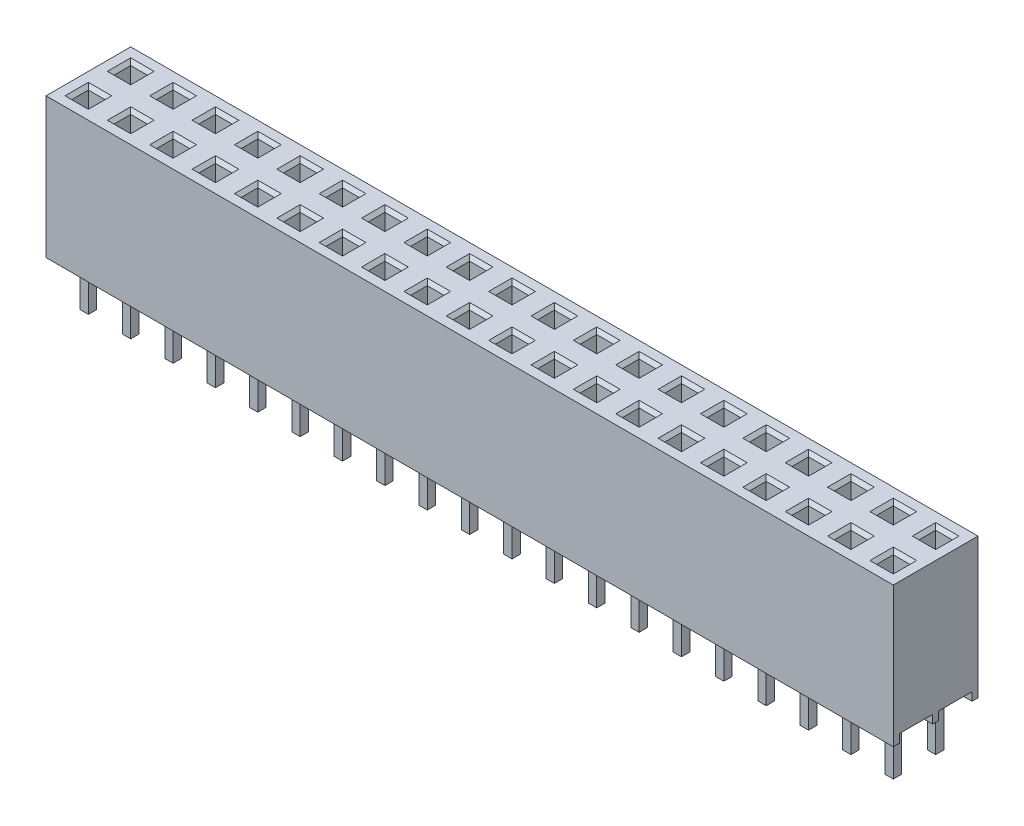
SolidWorks part; units mm, degrees
ref_plane "Спереди" through (0, 0, 0) normal (0, 0, 1) x (1, 0, 0)
ref_plane "Сверху" through (0, 0, 0) normal (0, 1, 0) x (1, 0, 0)
ref_plane "Справа" through (0, 0, 0) normal (1, 0, 0) x (0, 0, -1)
sketch "Эскиз1" plane through (0, 0, 0) normal (0, 1, 0) x (1, 0, 0)
  line L0 (0, 2.54) -> (0, -2.54) construction
  line L1 (-6.35, 2.54) -> (6.35, 2.54)
  line L2 (-6.35, 2.54) -> (-6.35, -2.54)
  line L3 (-6.35, -2.54) -> (6.35, -2.54)
  line L4 (6.35, 2.54) -> (6.35, -2.54)
  line L6 (6.35, 0) -> (-6.35, 0) construction
  dimension "D1" = 12.7
  dimension "D2" = 5.08
extrude "Бобышка-Вытянуть1" add sketch "Эскиз1" along normal blind 8.4
sketch "Эскиз2" plane through (6.35, 0, 0) normal (1, 0, 0) x (0, 0, -1)
  line L0 (-2.54, 0) -> (2.54, 0) construction
  line L1 (-2.18, 0) -> (-0.18, 0)
  line L2 (-2.18, 0) -> (-2.18, 0.5)
  line L3 (-2.18, 0.5) -> (-0.18, 0.5)
  line L4 (-0.18, 0) -> (-0.18, 0.5)
  line L5 (0, 0) -> (0, 8.4) construction
  line L6 (-2.54, 8.4) -> (-2.54, 0) construction
  line L10 (0.18, 0) -> (2.18, 0)
  line L11 (0.18, 0) -> (0.18, 0.5)
  line L12 (0.18, 0.5) -> (2.18, 0.5)
  line L13 (2.18, 0) -> (2.18, 0.5)
  line L14 (-2.54, 8.4) -> (2.54, 8.4) construction
  dimension "D1" = 0.5
  dimension "D2" = 0.36
  dimension "D3" = 0.36
extrude "Вырез-Вытянуть1" cut sketch "Эскиз2" against normal up to next
sketch "Эскиз3" plane through (0, 0.5, 0) normal (0, -1, 0) x (1, 0, 0)
  line L0 (-6.35, 0) -> (6.35, 0) construction
  line L1 (-6.35, 2.18) -> (-6.35, 0.18) construction
  line L3 (-5.08, 1.77) -> (-5.08, 0.77) construction
  line L4 (-5.58, 1.77) -> (-4.58, 1.77)
  line L5 (-5.58, 1.77) -> (-5.58, 0.77)
  line L6 (-5.58, 0.77) -> (-4.58, 0.77)
  line L7 (-4.58, 1.77) -> (-4.58, 0.77)
  line L8 (-5.58, 1.27) -> (-4.58, 1.27) construction
  line L9 (-6.35, -0.18) -> (-6.35, 0.18) construction
  line L10 (6.35, 0.18) -> (6.35, -0.18) construction
  line L11 (-5.58, -1.27) -> (-4.58, -1.27) construction
  line L12 (-5.08, -1.77) -> (-5.08, -0.77) construction
  line L13 (-4.58, -1.77) -> (-4.58, -0.77)
  line L14 (-5.58, -0.77) -> (-4.58, -0.77)
  line L15 (-5.58, -1.77) -> (-5.58, -0.77)
  line L16 (-5.58, -1.77) -> (-4.58, -1.77)
  line L17 (-3.04, 1.77) -> (-3.04, 0.77)
  line L18 (-3.04, 1.77) -> (-2.04, 1.77)
  line L19 (-2.04, 1.77) -> (-2.04, 0.77)
  line L20 (-3.04, 0.77) -> (-2.04, 0.77)
  line L21 (-3.04, -0.77) -> (-2.04, -0.77)
  line L22 (-3.04, -1.77) -> (-3.04, -0.77)
  line L23 (-3.04, -1.77) -> (-2.04, -1.77)
  line L24 (-2.04, -1.77) -> (-2.04, -0.77)
  line L25 (-0.5, 1.77) -> (-0.5, 0.77)
  line L26 (-0.5, 1.77) -> (0.5, 1.77)
  line L27 (0.5, 1.77) -> (0.5, 0.77)
  line L28 (-0.5, 0.77) -> (0.5, 0.77)
  line L29 (-0.5, -0.77) -> (0.5, -0.77)
  line L30 (-0.5, -1.77) -> (-0.5, -0.77)
  line L31 (-0.5, -1.77) -> (0.5, -1.77)
  line L32 (0.5, -1.77) -> (0.5, -0.77)
  line L33 (2.04, 1.77) -> (2.04, 0.77)
  line L34 (2.04, 1.77) -> (3.04, 1.77)
  line L35 (3.04, 1.77) -> (3.04, 0.77)
  line L36 (2.04, 0.77) -> (3.04, 0.77)
  line L37 (2.04, -0.77) -> (3.04, -0.77)
  line L38 (2.04, -1.77) -> (2.04, -0.77)
  line L39 (2.04, -1.77) -> (3.04, -1.77)
  line L40 (3.04, -1.77) -> (3.04, -0.77)
  line L41 (4.58, 1.77) -> (4.58, 0.77)
  line L42 (4.58, 1.77) -> (5.58, 1.77)
  line L43 (5.58, 1.77) -> (5.58, 0.77)
  line L44 (4.58, 0.77) -> (5.58, 0.77)
  line L45 (4.58, -0.77) -> (5.58, -0.77)
  line L46 (4.58, -1.77) -> (4.58, -0.77)
  line L47 (4.58, -1.77) -> (5.58, -1.77)
  line L48 (5.58, -1.77) -> (5.58, -0.77)
  line L49 (-5.58, 1.77) -> (-3.04, 1.77) construction
  dimension "D1" = 1
  dimension "D2" = 1
  dimension "D3" = 1.27
  dimension "D4" = 2.54
  dimension "D6" = 2.54
  dimension "D5" = 5
extrude "Вырез-Вытянуть2" cut sketch "Эскиз3" against normal up to next
chamfer "Фаска1" distance 0.2 angle 45 40 edges at (-5.08, 8.4, 1.77) (-4.58, 8.4, 1.27) (-5.08, 8.4, 0.77) (-5.58, 8.4, 1.27) (-2.04, 8.4, 1.27) (-2.54, 8.4, 0.77) (-3.04, 8.4, 1.27) (-2.54, 8.4, 1.77) (0.5, 8.4, 1.27) (0, 8.4, 0.77) (-0.5, 8.4, 1.27) (0, 8.4, 1.77) (3.04, 8.4, 1.27) (2.54, 8.4, 0.77) (2.04, 8.4, 1.27) (2.54, 8.4, 1.77) (5.58, 8.4, 1.27) (5.08, 8.4, 0.77) (4.58, 8.4, 1.27) (5.08, 8.4, 1.77) (5.08, 8.4, -1.77) (4.58, 8.4, -1.27) (5.08, 8.4, -0.77) (5.58, 8.4, -1.27) (2.54, 8.4, -1.77) (2.04, 8.4, -1.27) (2.54, 8.4, -0.77) (3.04, 8.4, -1.27) (0, 8.4, -1.77) (-0.5, 8.4, -1.27) (0, 8.4, -0.77) (0.5, 8.4, -1.27) (-2.54, 8.4, -1.77) (-3.04, 8.4, -1.27) (-2.54, 8.4, -0.77) (-2.04, 8.4, -1.27) (-5.58, 8.4, -1.27) (-5.08, 8.4, -0.77) (-4.58, 8.4, -1.27) (-5.08, 8.4, -1.77)
pattern_linear "Линейный массив3" count 4 spacing 12.7 along (1, 0, 0) of "Бобышка-Вытянуть1", "Вырез-Вытянуть1", "Фаска1", "Вырез-Вытянуть2"
sketch "Эскиз4" plane through (0, 0.5, 0) normal (0, -1, 0) x (1, 0, 0)
  line L0 (-5.08, 1.52) -> (-5.08, 1.02) construction
  line L1 (-5.33, 1.52) -> (-4.83, 1.52)
  line L2 (-5.33, 1.52) -> (-5.33, 1.02)
  line L3 (-5.33, 1.02) -> (-4.83, 1.02)
  line L4 (-4.83, 1.52) -> (-4.83, 1.02)
  line L5 (-5.33, -1.27) -> (-4.83, -1.27) construction
  line L6 (-5.33, 1.27) -> (-4.83, 1.27) construction
  line L7 (-5.08, -1.52) -> (-5.08, -1.02) construction
  line L8 (-6.35, -0.18) -> (-6.35, 0.18) construction
  line L9 (-6.35, 0) -> (44.45, 0) construction
  line L11 (-4.83, -1.52) -> (-4.83, -1.02)
  line L12 (-5.33, -1.02) -> (-4.83, -1.02)
  line L13 (-5.33, -1.52) -> (-5.33, -1.02)
  line L14 (-5.33, -1.52) -> (-4.83, -1.52)
  line L15 (-6.35, 2.18) -> (-6.35, 0.18) construction
  line L16 (-2.79, 1.52) -> (-2.79, 1.02)
  line L17 (-2.79, 1.52) -> (-2.29, 1.52)
  line L18 (-2.79, 1.02) -> (-2.29, 1.02)
  line L19 (-2.29, 1.52) -> (-2.29, 1.02)
  line L20 (-2.79, -1.52) -> (-2.29, -1.52)
  line L21 (-2.79, -1.52) -> (-2.79, -1.02)
  line L22 (-2.79, -1.02) -> (-2.29, -1.02)
  line L23 (-2.29, -1.52) -> (-2.29, -1.02)
  line L24 (-0.25, 1.52) -> (-0.25, 1.02)
  line L25 (-0.25, 1.52) -> (0.25, 1.52)
  line L26 (-0.25, 1.02) -> (0.25, 1.02)
  line L27 (0.25, 1.52) -> (0.25, 1.02)
  line L28 (-0.25, -1.52) -> (0.25, -1.52)
  line L29 (-0.25, -1.52) -> (-0.25, -1.02)
  line L30 (-0.25, -1.02) -> (0.25, -1.02)
  line L31 (0.25, -1.52) -> (0.25, -1.02)
  line L32 (2.29, 1.52) -> (2.29, 1.02)
  line L33 (2.29, 1.52) -> (2.79, 1.52)
  line L34 (2.29, 1.02) -> (2.79, 1.02)
  line L35 (2.79, 1.52) -> (2.79, 1.02)
  line L36 (2.29, -1.52) -> (2.79, -1.52)
  line L37 (2.29, -1.52) -> (2.29, -1.02)
  line L38 (2.29, -1.02) -> (2.79, -1.02)
  line L39 (2.79, -1.52) -> (2.79, -1.02)
  line L40 (4.83, 1.52) -> (4.83, 1.02)
  line L41 (4.83, 1.52) -> (5.33, 1.52)
  line L42 (4.83, 1.02) -> (5.33, 1.02)
  line L43 (5.33, 1.52) -> (5.33, 1.02)
  line L44 (4.83, -1.52) -> (5.33, -1.52)
  line L45 (4.83, -1.52) -> (4.83, -1.02)
  line L46 (4.83, -1.02) -> (5.33, -1.02)
  line L47 (5.33, -1.52) -> (5.33, -1.02)
  line L48 (-5.33, 1.52) -> (-2.79, 1.52) construction
  line L50 (7.37, 1.52) -> (7.37, 1.02)
  line L51 (7.37, 1.52) -> (7.87, 1.52)
  line L52 (7.37, 1.02) -> (7.87, 1.02)
  line L53 (7.87, 1.52) -> (7.87, 1.02)
  line L54 (7.37, -1.52) -> (7.87, -1.52)
  line L55 (7.37, -1.52) -> (7.37, -1.02)
  line L56 (7.37, -1.02) -> (7.87, -1.02)
  line L57 (7.87, -1.52) -> (7.87, -1.02)
  line L58 (9.91, 1.52) -> (9.91, 1.02)
  line L59 (9.91, 1.52) -> (10.41, 1.52)
  line L60 (9.91, 1.02) -> (10.41, 1.02)
  line L61 (10.41, 1.52) -> (10.41, 1.02)
  line L62 (9.91, -1.52) -> (10.41, -1.52)
  line L63 (9.91, -1.52) -> (9.91, -1.02)
  line L64 (9.91, -1.02) -> (10.41, -1.02)
  line L65 (10.41, -1.52) -> (10.41, -1.02)
  line L66 (12.45, 1.52) -> (12.45, 1.02)
  line L67 (12.45, 1.52) -> (12.95, 1.52)
  line L68 (12.45, 1.02) -> (12.95, 1.02)
  line L69 (12.95, 1.52) -> (12.95, 1.02)
  line L70 (12.45, -1.52) -> (12.95, -1.52)
  line L71 (12.45, -1.52) -> (12.45, -1.02)
  line L72 (12.45, -1.02) -> (12.95, -1.02)
  line L73 (12.95, -1.52) -> (12.95, -1.02)
  line L74 (14.99, 1.52) -> (14.99, 1.02)
  line L75 (14.99, 1.52) -> (15.49, 1.52)
  line L76 (14.99, 1.02) -> (15.49, 1.02)
  line L77 (15.49, 1.52) -> (15.49, 1.02)
  line L78 (14.99, -1.52) -> (15.49, -1.52)
  line L79 (14.99, -1.52) -> (14.99, -1.02)
  line L80 (14.99, -1.02) -> (15.49, -1.02)
  line L81 (15.49, -1.52) -> (15.49, -1.02)
  line L82 (17.53, 1.52) -> (17.53, 1.02)
  line L83 (17.53, 1.52) -> (18.03, 1.52)
  line L84 (17.53, 1.02) -> (18.03, 1.02)
  line L85 (18.03, 1.52) -> (18.03, 1.02)
  line L86 (17.53, -1.52) -> (18.03, -1.52)
  line L87 (17.53, -1.52) -> (17.53, -1.02)
  line L88 (17.53, -1.02) -> (18.03, -1.02)
  line L89 (18.03, -1.52) -> (18.03, -1.02)
  line L90 (44.45, 0.18) -> (44.45, -0.18) construction
  line L91 (20.07, 1.52) -> (20.07, 1.02)
  line L92 (20.07, 1.52) -> (20.57, 1.52)
  line L93 (20.07, 1.02) -> (20.57, 1.02)
  line L94 (20.57, 1.52) -> (20.57, 1.02)
  line L95 (20.07, -1.52) -> (20.57, -1.52)
  line L96 (20.07, -1.52) -> (20.07, -1.02)
  line L97 (20.07, -1.02) -> (20.57, -1.02)
  line L98 (20.57, -1.52) -> (20.57, -1.02)
  line L99 (22.61, 1.52) -> (22.61, 1.02)
  line L100 (22.61, 1.52) -> (23.11, 1.52)
  line L101 (22.61, 1.02) -> (23.11, 1.02)
  line L102 (23.11, 1.52) -> (23.11, 1.02)
  line L103 (22.61, -1.52) -> (23.11, -1.52)
  line L104 (22.61, -1.52) -> (22.61, -1.02)
  line L105 (22.61, -1.02) -> (23.11, -1.02)
  line L106 (23.11, -1.52) -> (23.11, -1.02)
  line L107 (25.15, 1.52) -> (25.15, 1.02)
  line L108 (25.15, 1.52) -> (25.65, 1.52)
  line L109 (25.15, 1.02) -> (25.65, 1.02)
  line L110 (25.65, 1.52) -> (25.65, 1.02)
  line L111 (25.15, -1.52) -> (25.65, -1.52)
  line L112 (25.15, -1.52) -> (25.15, -1.02)
  line L113 (25.15, -1.02) -> (25.65, -1.02)
  line L114 (25.65, -1.52) -> (25.65, -1.02)
  line L115 (27.69, 1.52) -> (27.69, 1.02)
  line L116 (27.69, 1.52) -> (28.19, 1.52)
  line L117 (27.69, 1.02) -> (28.19, 1.02)
  line L118 (28.19, 1.52) -> (28.19, 1.02)
  line L119 (27.69, -1.52) -> (28.19, -1.52)
  line L120 (27.69, -1.52) -> (27.69, -1.02)
  line L121 (27.69, -1.02) -> (28.19, -1.02)
  line L122 (28.19, -1.52) -> (28.19, -1.02)
  line L123 (30.23, 1.52) -> (30.23, 1.02)
  line L124 (30.23, 1.52) -> (30.73, 1.52)
  line L125 (30.23, 1.02) -> (30.73, 1.02)
  line L126 (30.73, 1.52) -> (30.73, 1.02)
  line L127 (30.23, -1.52) -> (30.73, -1.52)
  line L128 (30.23, -1.52) -> (30.23, -1.02)
  line L129 (30.23, -1.02) -> (30.73, -1.02)
  line L130 (30.73, -1.52) -> (30.73, -1.02)
  line L131 (32.77, 1.52) -> (32.77, 1.02)
  line L132 (32.77, 1.52) -> (33.27, 1.52)
  line L133 (32.77, 1.02) -> (33.27, 1.02)
  line L134 (33.27, 1.52) -> (33.27, 1.02)
  line L135 (32.77, -1.52) -> (33.27, -1.52)
  line L136 (32.77, -1.52) -> (32.77, -1.02)
  line L137 (32.77, -1.02) -> (33.27, -1.02)
  line L138 (33.27, -1.52) -> (33.27, -1.02)
  line L139 (35.31, 1.52) -> (35.31, 1.02)
  line L140 (35.31, 1.52) -> (35.81, 1.52)
  line L141 (35.31, 1.02) -> (35.81, 1.02)
  line L142 (35.81, 1.52) -> (35.81, 1.02)
  line L143 (35.31, -1.52) -> (35.81, -1.52)
  line L144 (35.31, -1.52) -> (35.31, -1.02)
  line L145 (35.31, -1.02) -> (35.81, -1.02)
  line L146 (35.81, -1.52) -> (35.81, -1.02)
  line L147 (37.85, 1.52) -> (37.85, 1.02)
  line L148 (37.85, 1.52) -> (38.35, 1.52)
  line L149 (37.85, 1.02) -> (38.35, 1.02)
  line L150 (38.35, 1.52) -> (38.35, 1.02)
  line L151 (37.85, -1.52) -> (38.35, -1.52)
  line L152 (37.85, -1.52) -> (37.85, -1.02)
  line L153 (37.85, -1.02) -> (38.35, -1.02)
  line L154 (38.35, -1.52) -> (38.35, -1.02)
  line L155 (40.39, 1.52) -> (40.39, 1.02)
  line L156 (40.39, 1.52) -> (40.89, 1.52)
  line L157 (40.39, 1.02) -> (40.89, 1.02)
  line L158 (40.89, 1.52) -> (40.89, 1.02)
  line L159 (40.39, -1.52) -> (40.89, -1.52)
  line L160 (40.39, -1.52) -> (40.39, -1.02)
  line L161 (40.39, -1.02) -> (40.89, -1.02)
  line L162 (40.89, -1.52) -> (40.89, -1.02)
  line L163 (42.93, 1.52) -> (42.93, 1.02)
  line L164 (42.93, 1.52) -> (43.43, 1.52)
  line L165 (42.93, 1.02) -> (43.43, 1.02)
  line L166 (43.43, 1.52) -> (43.43, 1.02)
  line L167 (42.93, -1.52) -> (43.43, -1.52)
  line L168 (42.93, -1.52) -> (42.93, -1.02)
  line L169 (42.93, -1.02) -> (43.43, -1.02)
  line L170 (43.43, -1.52) -> (43.43, -1.02)
  dimension "D1" = 2.54
  dimension "D2" = 0.5
  dimension "D3" = 1.27
  dimension "D5" = 2.54
  dimension "D4" = 20
extrude "Бобышка-Вытянуть2" add sketch "Эскиз4" along normal blind 3.2 and the other way blind 3.2 separate body
